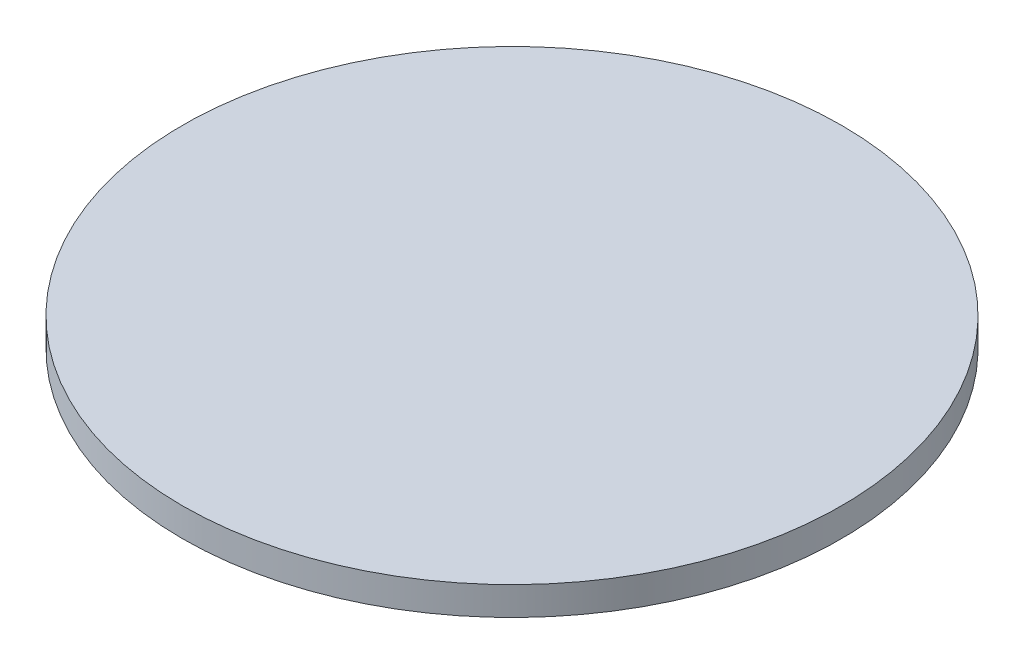
SolidWorks part; units mm, degrees
ref_plane "Front Plane" through (0, 0, 0) normal (0, 0, 1) x (1, 0, 0)
ref_plane "Top Plane" through (0, 0, 0) normal (0, 1, 0) x (1, 0, 0)
ref_plane "Right Plane" through (0, 0, 0) normal (1, 0, 0) x (0, 0, -1)
sketch "Sketch1" plane through (0, 0, 0) normal (0, 1, 0) x (1, 0, 0)
  circle A0 centre (0, 0) radius 23.495
  dimension "D1" = 46.99
extrude "Boss-Extrude1" add sketch "Sketch1" along normal blind 2.032
